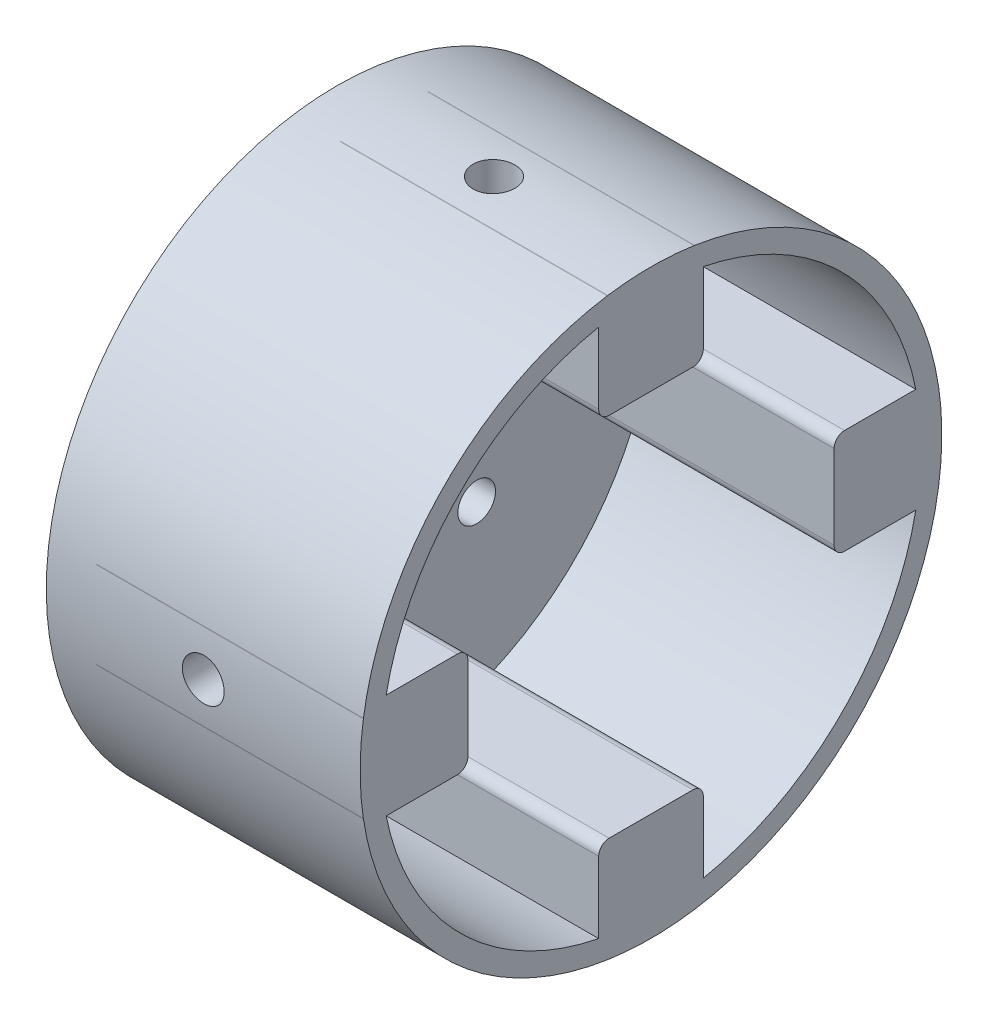
SolidWorks part; units mm, degrees
ref_plane "Front Plane" through (0, 0, 0) normal (0, 0, 1) x (1, 0, 0)
ref_plane "Top Plane" through (0, 0, 0) normal (0, 1, 0) x (1, 0, 0)
ref_plane "Right Plane" through (0, 0, 0) normal (1, 0, 0) x (0, 0, -1)
sketch "Sketch1" plane through (0, 0, 0) normal (0, 0, 1) x (1, 0, 0)
  line L0 (0, 0) -> (0, 27.8)
  line L1 (0, 27.8) -> (30, 27.8)
  line L2 (30, 27.8) -> (30, 25.8)
  line L3 (30, 25.8) -> (4.5, 25.8)
  line L4 (4.5, 25.8) -> (4.5, 0)
  line L5 (4.5, 0) -> (0, 0)
  line L6 (-10, 0) -> (1000, 0) construction
revolve "Revolve1" add sketch "Sketch1" angle 360 about L6
ref_plane "Plane1" through (4.5, 0, 0) normal (1, 0, 0) x (0, 0, -1)
sketch "Sketch2" plane through (4.5, 0, 0) normal (1, 0, 0) x (0, 0, -1)
  line L0 (-4, 17.5) -> (4, 17.5)
  line L1 (5, 18.5) -> (5, 26.5)
  line L2 (4, 27.5) -> (-4, 27.5)
  line L3 (-5, 26.5) -> (-5, 18.5)
  line L4 (-4, -27.5) -> (4, -27.5)
  line L5 (5, -26.5) -> (5, -18.5)
  line L6 (4, -17.5) -> (-4, -17.5)
  line L7 (-5, -18.5) -> (-5, -26.5)
  line L8 (-26.5, -5) -> (-18.5, -5)
  line L9 (-17.5, -4) -> (-17.5, 4)
  line L10 (-18.5, 5) -> (-26.5, 5)
  line L11 (-27.5, 4) -> (-27.5, -4)
  line L12 (18.5, -5) -> (26.5, -5)
  line L13 (27.5, -4) -> (27.5, 4)
  line L14 (26.5, 5) -> (18.5, 5)
  line L15 (17.5, 4) -> (17.5, -4)
  arc A0 (4, 17.5) -> (5, 18.5) centre (4, 18.5) ccw
  arc A1 (5, 26.5) -> (4, 27.5) centre (4, 26.5) ccw
  arc A2 (-4, 27.5) -> (-5, 26.5) centre (-4, 26.5) ccw
  arc A3 (-5, 18.5) -> (-4, 17.5) centre (-4, 18.5) ccw
  arc A4 (4, -27.5) -> (5, -26.5) centre (4, -26.5) ccw
  arc A5 (5, -18.5) -> (4, -17.5) centre (4, -18.5) ccw
  arc A6 (-4, -17.5) -> (-5, -18.5) centre (-4, -18.5) ccw
  arc A7 (-5, -26.5) -> (-4, -27.5) centre (-4, -26.5) ccw
  arc A8 (-18.5, -5) -> (-17.5, -4) centre (-18.5, -4) ccw
  arc A9 (-17.5, 4) -> (-18.5, 5) centre (-18.5, 4) ccw
  arc A10 (-26.5, 5) -> (-27.5, 4) centre (-26.5, 4) ccw
  arc A11 (-27.5, -4) -> (-26.5, -5) centre (-26.5, -4) ccw
  arc A12 (26.5, -5) -> (27.5, -4) centre (26.5, -4) ccw
  arc A13 (27.5, 4) -> (26.5, 5) centre (26.5, 4) ccw
  arc A14 (18.5, 5) -> (17.5, 4) centre (18.5, 4) ccw
  arc A15 (17.5, -4) -> (18.5, -5) centre (18.5, -4) ccw
extrude "Boss-Extrude1" add sketch "Sketch2" along normal blind 25.5
sketch "Sketch3" plane through (0, 0, 0) normal (1, 0, 0) x (0, 0, -1)
  circle A0 centre (-8.84, 8.84) radius 1.8
  circle A1 centre (-8.84, -8.84) radius 1.8
  circle A2 centre (8.84, 8.84) radius 1.8
  circle A3 centre (8.84, -8.84) radius 1.8
extrude "Cut-Extrude1" cut sketch "Sketch3" along normal blind 4.5
sketch "Sketch4" plane through (0, 0, 0) normal (1, 0, 0) x (0, 0, -1)
  circle A0 centre (0, 0) radius 4
extrude "Cut-Extrude2" cut sketch "Sketch4" along normal blind 2
sketch "Sketch5" plane through (0, 0, 0) normal (1, 0, 0) x (0, 0, -1)
  line L0 (3, -28) -> (-3, -28)
  line L1 (-3, -28) -> (-3, -3)
  line L2 (-3, -3) -> (3, -3)
  line L3 (3, -3) -> (3, -28)
extrude "Cut-Extrude3" cut sketch "Sketch5" along normal blind 2
ref_plane "Plane2" through (0, 27.8, 0) normal (0, 1, 0) x (1, 0, 0)
sketch "Sketch6" plane through (0, 27.8, 0) normal (0, 1, 0) x (1, 0, 0)
  circle A0 centre (15, 0) radius 2
extrude "Cut-Extrude4" cut sketch "Sketch6" against normal blind 7
ref_plane "Plane3" through (0, -27.8, 0) normal (0, 1, 0) x (1, 0, 0)
sketch "Sketch7" plane through (0, -27.8, 0) normal (0, 1, 0) x (1, 0, 0)
  circle A0 centre (15, 0) radius 2
extrude "Cut-Extrude5" cut sketch "Sketch7" along normal blind 7
ref_plane "Plane4" through (0, 0, 27.8) normal (0, 0, 1) x (1, 0, 0)
sketch "Sketch8" plane through (0, 0, 27.8) normal (0, 0, 1) x (1, 0, 0)
  circle A0 centre (15, 0) radius 2
extrude "Cut-Extrude6" cut sketch "Sketch8" against normal blind 7
ref_plane "Plane5" through (0, 0, -27.8) normal (0, 0, 1) x (1, 0, 0)
sketch "Sketch9" plane through (0, 0, -27.8) normal (0, 0, 1) x (1, 0, 0)
  circle A0 centre (15, 0) radius 2
extrude "Cut-Extrude7" cut sketch "Sketch9" along normal blind 7
